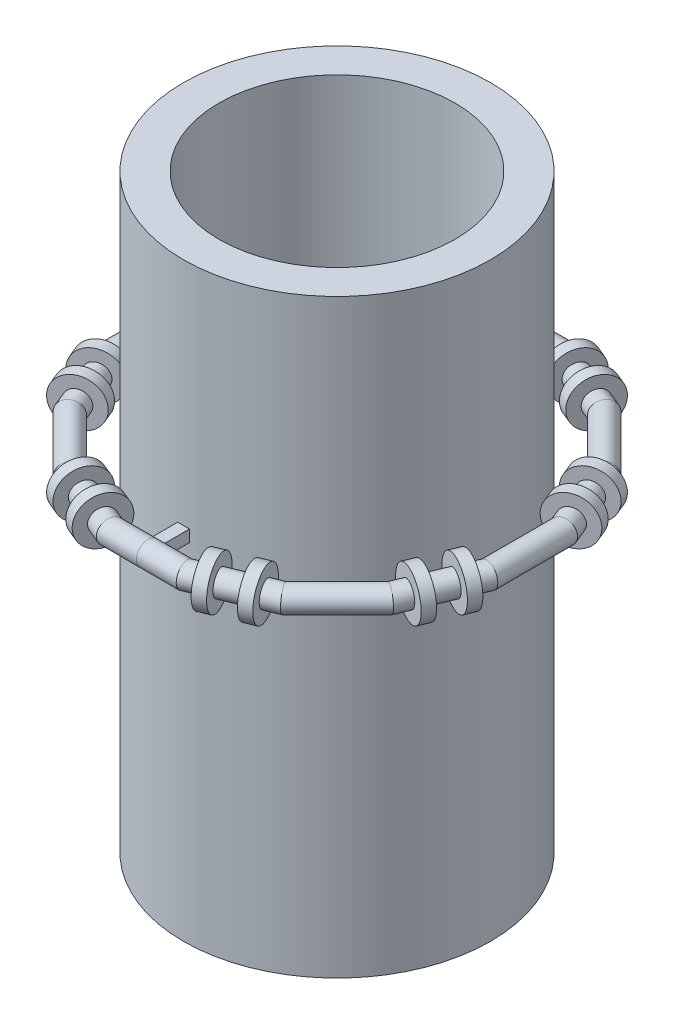
SolidWorks part; units mm, degrees
ref_plane "Alzado" through (0, 0, 0) normal (0, 0, 1) x (1, 0, 0)
ref_plane "Planta" through (0, 0, 0) normal (0, 1, 0) x (1, 0, 0)
ref_plane "Vista lateral" through (0, 0, 0) normal (1, 0, 0) x (0, 0, -1)
sketch "Croquis1" plane through (0, 0, 0) normal (0, 1, 0) x (1, 0, 0)
  circle A0 centre (0, 0) radius 6.5
  circle A1 centre (0, 0) radius 5
  dimension "D1" = 13
  dimension "D2" = 10
extrude "Saliente-Extruir1" add sketch "Croquis1" along normal blind 25
ref_plane "Plano1" through (0, 15, 0) normal (0, 1, 0) x (1, 0, 0)
sketch "Croquis2" plane through (0, 15, 0) normal (0, 1, 0) x (1, 0, 0)
  line L1 (-4.5316, -6.7821) -> (-1.5913, -8)
  line L2 (-1.5913, -8) -> (1.5913, -8)
  line L3 (1.5913, -8) -> (4.5316, -6.7821)
  line L4 (4.5316, -6.7821) -> (6.7821, -4.5316)
  line L5 (6.7821, -4.5316) -> (8, -1.5913)
  line L6 (8, -1.5913) -> (8, 1.5913)
  line L7 (8, 1.5913) -> (6.7821, 4.5316)
  line L8 (6.7821, 4.5316) -> (4.5316, 6.7821)
  line L9 (4.5316, 6.7821) -> (1.5913, 8)
  line L10 (1.5913, 8) -> (-1.5913, 8)
  line L11 (-1.5913, 8) -> (-4.5316, 6.7821)
  line L12 (-4.5316, 6.7821) -> (-6.7821, 4.5316)
  line L13 (-6.7821, 4.5316) -> (-8, 1.5913)
  line L14 (-8, 1.5913) -> (-8, -1.5913)
  line L15 (-8, -1.5913) -> (-6.7821, -4.5316)
  line L16 (-6.7821, -4.5316) -> (-4.5316, -6.7821)
  circle A0 centre (0, 0) radius 8 construction
  point P21 (0, 8)
  dimension "D1" = 8
sketch "Croquis3" plane through (0, 0, 0) normal (1, 0, 0) x (0, 0, -1)
  circle A0 centre (-8, 15) radius 0.5
  dimension "D1" = 1
sweep "Barrer1" add profiles "Croquis3" path "Croquis2"
ref_plane "Plano2" through (0, 0, 6) normal (0, 0, 1) x (1, 0, 0)
sketch "Croquis4" plane through (0, 0, 6) normal (0, 0, 1) x (1, 0, 0)
  line L0 (0, 15.5) -> (0, 14.5) construction
  line L1 (0.25, 15.25) -> (-0.25, 15.25)
  line L2 (0.25, 15.25) -> (0.25, 14.75)
  line L3 (0.25, 14.75) -> (-0.25, 14.75)
  line L4 (-0.25, 15.25) -> (-0.25, 14.75)
  line L5 (0.25, 15.25) -> (-0.25, 14.75) construction
  line L6 (0.25, 14.75) -> (-0.25, 15.25) construction
  point P0 (0, 15)
  dimension "D1" = 0.5
extrude "Saliente-Extruir2" add sketch "Croquis4" along normal up to surface (1.567 mm away)
ref_plane "Plano3" through (0, 0, -6) normal (0, 0, 1) x (1, 0, 0)
sketch "Croquis6" plane through (0, 0, -6) normal (0, 0, 1) x (1, 0, 0)
  line L4 (0.25, 15.25) -> (-0.25, 15.25)
  line L5 (-0.25, 15.25) -> (-0.25, 14.75)
  line L6 (-0.25, 14.75) -> (0.25, 14.75)
  line L7 (0.25, 14.75) -> (0.25, 15.25)
  line L8 (0.25, 15.25) -> (-0.25, 15.25)
  line L9 (-0.25, 15.25) -> (-0.25, 14.75)
  line L10 (-0.25, 14.75) -> (0.25, 14.75)
  line L11 (0.25, 14.75) -> (0.25, 15.25)
  dimension "D1" = 0
extrude "Saliente-Extruir3" add sketch "Croquis6" against normal up to surface (1.567 mm away)
sketch "Croquis7" plane through (0, 25, 0) normal (0, 1, 0) x (1, 0, 0)
  line L0 (0, -4.0488) -> (0, 0) construction
  line L1 (0, 0) -> (-3.9012, -9.4184) construction
  dimension "D1" = 22.5
ref_plane "Plano4" through (0, 0, 0) normal (-0.9239, 0, -0.3827) x (-0.3827, 0, 0.9239)
ref_plane "Plano5" through (-0.4619, 0, -0.1913) normal (-0.9239, 0, -0.3827) x (-0.3827, 0, 0.9239)
sketch "Croquis9" plane through (-0.4619, 0, -0.1913) normal (-0.9239, 0, -0.3827) x (-0.3827, 0, 0.9239)
  circle A0 centre (8, 15) radius 1
  dimension "D1" = 2
extrude "Saliente-Extruir4" add sketch "Croquis9" along normal blind 0.5
mirror "Simetría1" about plane through (0, 0, 0) normal (-0.9239, 0, -0.3827) of "Saliente-Extruir4"
mirror "Simetría2" about plane through (0, 0, 0) normal (0, 0, 1) of "Simetría1", "Saliente-Extruir4"
mirror "Simetría3" about plane through (0, 0, 0) normal (1, 0, 0) of "Simetría2", "Saliente-Extruir4", "Simetría1"
mirror "Simetría4" about plane through (0, 0, 0) normal (-0.9239, 0, -0.3827) of "Simetría3", "Simetría2"
mirror "Simetría5" about plane through (0, 0, 0) normal (1, 0, 0) of "Simetría4"
